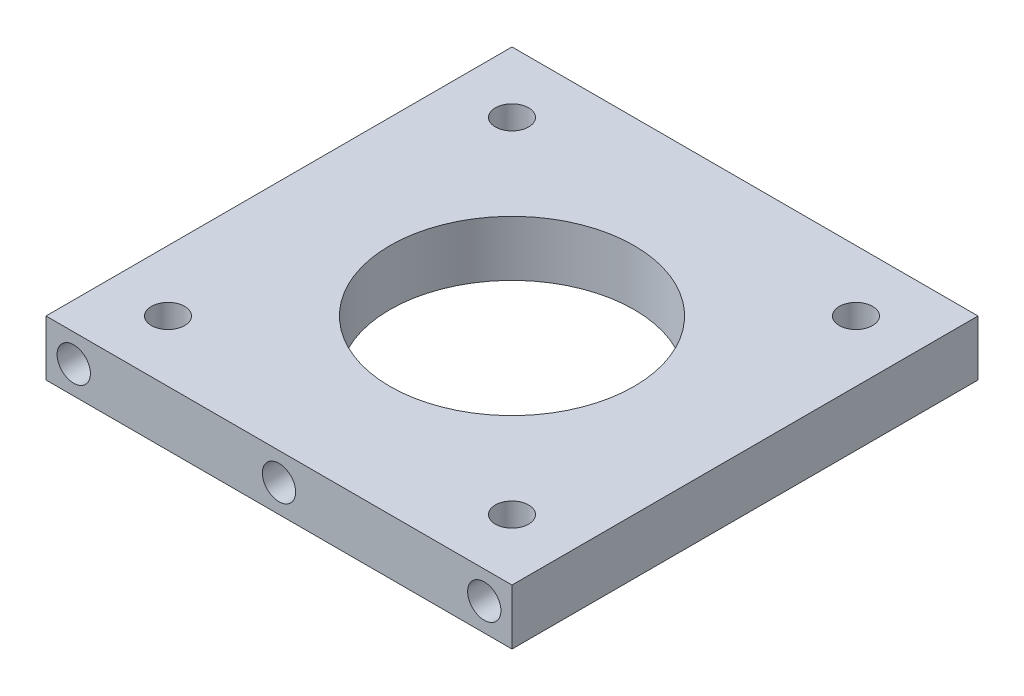
SolidWorks part; units mm, degrees
material "3003 합금"
ref_plane "정면" through (0, 0, 0) normal (0, 0, 1) x (1, 0, 0)
ref_plane "윗면" through (0, 0, 0) normal (0, 1, 0) x (1, 0, 0)
ref_plane "우측면" through (0, 0, 0) normal (1, 0, 0) x (0, 0, -1)
sketch "스케치1" plane through (0, 0, 0) normal (0, 1, 0) x (1, 0, 0)
  line L1 (-21, -21) -> (21, -21)
  line L2 (-21, -21) -> (-21, 21)
  line L3 (-21, 21) -> (21, 21)
  line L4 (21, -21) -> (21, 21)
  line L5 (-21, -21) -> (21, 21) construction
  line L6 (-21, 21) -> (21, -21) construction
  point P1 (0, 0)
  dimension "D1" = 42
  dimension "D2" = 42
  dimension "D3" = 21
  dimension "D4" = 21
extrude "보스-돌출1" add sketch "스케치1" along normal blind 5
sketch "스케치2" plane through (0, 0, 21) normal (0, 0, 1) x (1, 0, 0)
  line L0 (-21, 0) -> (21, 0) construction
  line L1 (-21, 5) -> (-21, 0) construction
  line L2 (21, 5) -> (21, 0) construction
  line L3 (-18.5, 2.5) -> (18.5, 2.5) construction
  circle A0 centre (-18.5, 2.5) radius 1.5
  circle A1 centre (18.5, 2.5) radius 1.5
  circle A2 centre (0, 2.5) radius 1.5
  dimension "D1" = 2.5
  dimension "D3" = 2.5
  dimension "D5" = 18.5
  dimension "D2" = 2.5
  dimension "D4" = 2.5
sketch "스케치3" plane through (0, 5, 0) normal (0, 1, 0) x (1, 0, 0)
  line L0 (21, 21) -> (-21, 21) construction
  line L1 (-21, 21) -> (-21, -21) construction
  line L2 (21, -21) -> (21, 21) construction
  circle A0 centre (0, 0) radius 11
  circle A1 centre (-15.5, 15.5) radius 1.5
  circle A2 centre (15.5, 15.4996) radius 1.5
  circle A3 centre (15.4996, -15.5004) radius 1.5
  circle A4 centre (-15.5004, -15.5) radius 1.5
  point P17 (-0.0002, -0.0002)
  dimension "D1" = 21
  dimension "D3" = 5.5
  dimension "D9" = 22
  dimension "D2" = 21
  dimension "D4" = 5.5
  dimension "D6" = 5.5004
  dimension "D7" = 31
  dimension "D8" = 31
  dimension "D5" = 4
extrude "컷-돌출1" cut sketch "스케치3" against normal through all
extrude "컷-돌출3" cut sketch "스케치2" against normal blind 4 contours A0 | A1 | A2
